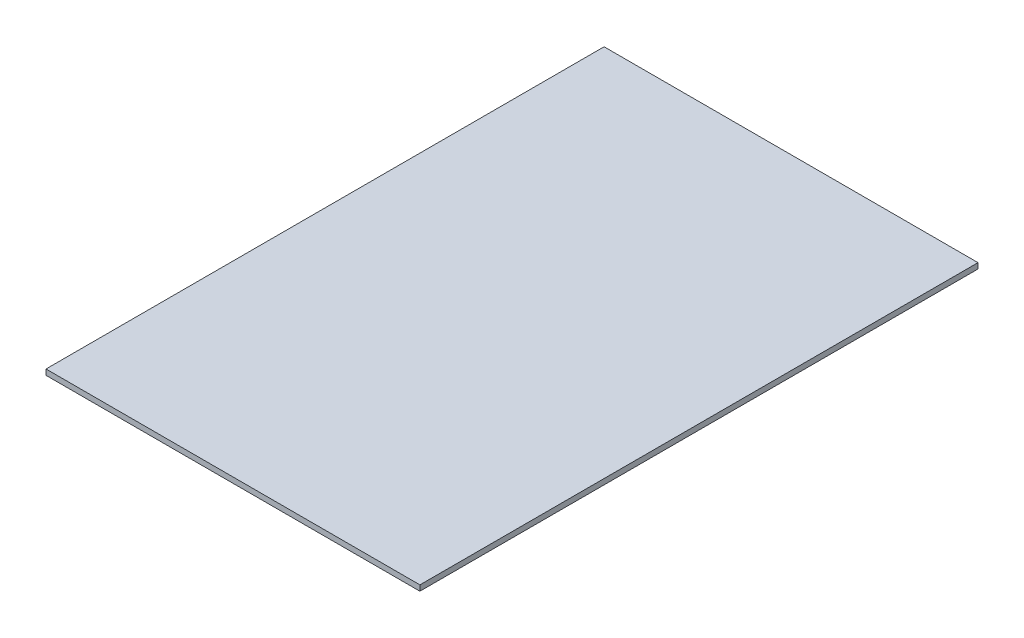
SolidWorks part; units mm, degrees
material "有机玻璃 (TM) GS 丙烯酸铸钣"
ref_plane "前视基准面" through (0, 0, 0) normal (0, 0, 1) x (1, 0, 0)
ref_plane "上视基准面" through (0, 0, 0) normal (0, 1, 0) x (1, 0, 0)
ref_plane "右视基准面" through (0, 0, 0) normal (1, 0, 0) x (0, 0, -1)
sketch "草图1" plane through (0, 0, 0) normal (0, 1, 0) x (1, 0, 0)
  line L1 (-101.5, 151.5) -> (101.5, 151.5)
  line L2 (-101.5, 151.5) -> (-101.5, -151.5)
  line L3 (-101.5, -151.5) -> (101.5, -151.5)
  line L4 (101.5, 151.5) -> (101.5, -151.5)
  line L5 (-101.5, 151.5) -> (101.5, -151.5) construction
  line L6 (-101.5, -151.5) -> (101.5, 151.5) construction
  point P0 (0, 0)
  dimension "D1" = 303
  dimension "D2" = 203
extrude "凸台-拉伸1" add sketch "草图1" along normal blind 3
